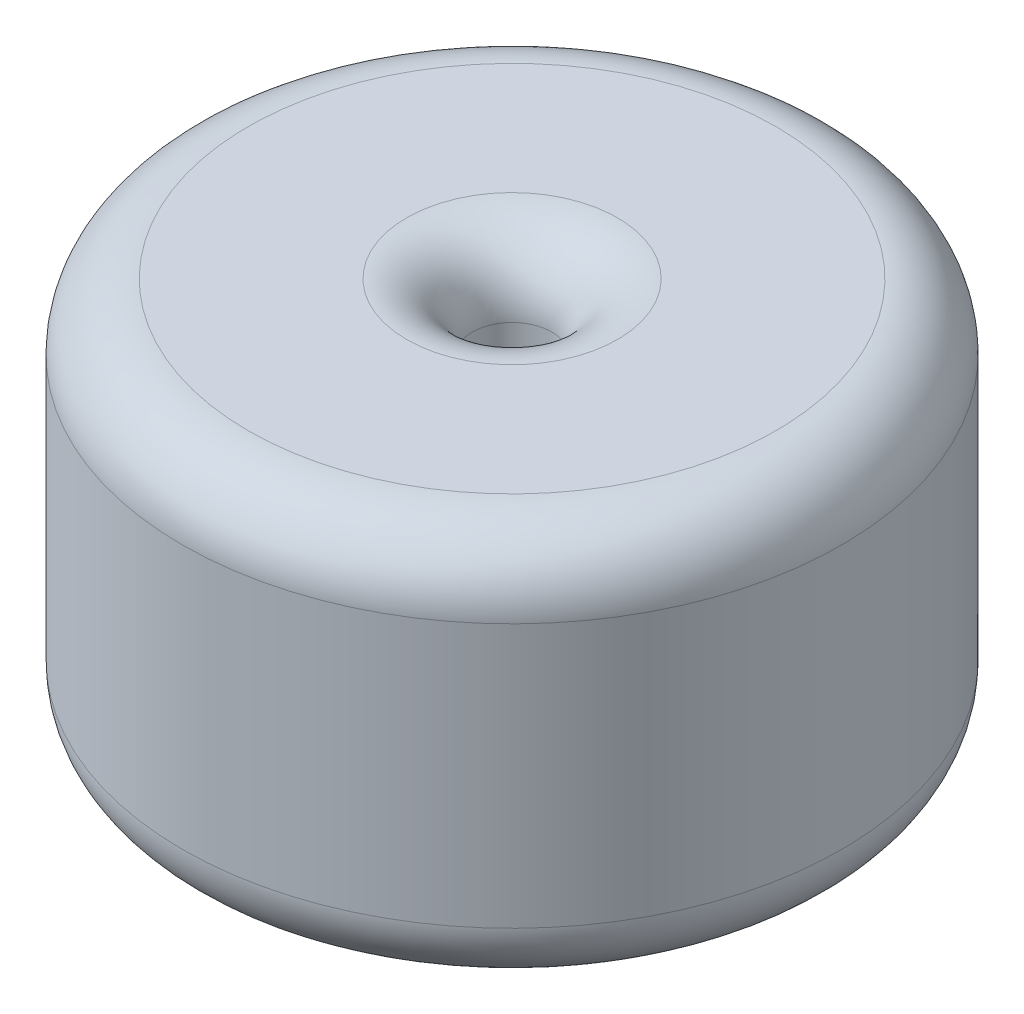
SolidWorks part; units mm, degrees
ref_plane "前基準面" through (0, 0, 0) normal (0, 0, 1) x (1, 0, 0)
ref_plane "上基準面" through (0, 0, 0) normal (0, 1, 0) x (1, 0, 0)
ref_plane "右基準面" through (0, 0, 0) normal (1, 0, 0) x (0, 0, -1)
sketch "草圖1" plane through (0, 0, 0) normal (0, 1, 0) x (1, 0, 0)
  circle A0 centre (0, 0) radius 25
  circle A1 centre (0, 0) radius 3
  dimension "D1" = 50
  dimension "D2" = 6
extrude "伸長1" add sketch "草圖1" along normal blind 30
fillet "圓角1" radius 5 3 edges at (0, 30, 25) (0, 0, 3) (0, 30, 3)
fillet "圓角2" radius 5 1 edges at (0, 0, 25)
